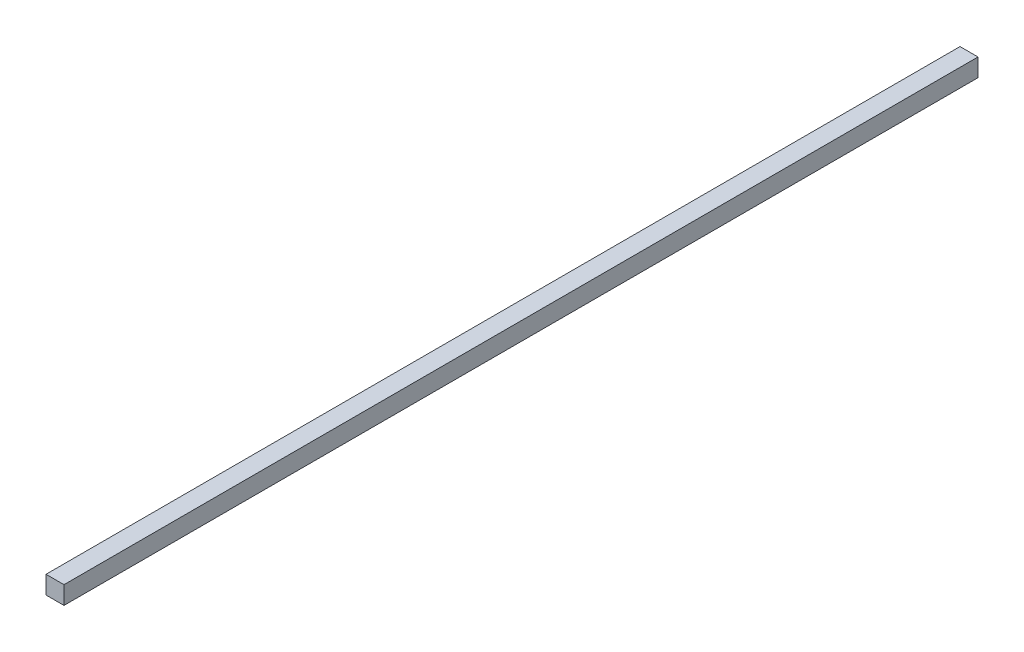
SolidWorks part; units mm, degrees
ref_plane "Front Plane" through (0, 0, 0) normal (0, 0, 1) x (1, 0, 0)
ref_plane "Top Plane" through (0, 0, 0) normal (0, 1, 0) x (1, 0, 0)
ref_plane "Right Plane" through (0, 0, 0) normal (1, 0, 0) x (0, 0, -1)
sketch "Sketch1" plane through (0, 0, 0) normal (0, 0, 1) x (1, 0, 0)
  line L0 (-3, 0) -> (3, 0) construction
  line L1 (0, -3) -> (0, 3) construction
  line L5 (-3, 3) -> (3, 3) construction
  line L7 (-3, 3) -> (-3, -3) construction
  line L8 (3, -3) -> (3, 3) construction
  line L13 (-3, -3) -> (3, -3) construction
  point P0 (0, 0)
  point P4 (0, 0)
  point P9 (0, 0)
  point P22 (0, 3)
  dimension "Thickness" = 6
  dimension "D1" = 6
sketch "Sketch2" plane through (0, 0, 0) normal (0, 1, 0) x (0, 0, -1)
  line L0 (152.4, 0) -> (-152.4, 0) construction
  line L2 (-152.4, 3) -> (152.4, 3) construction
  line L3 (-152.4, 3) -> (-152.4, -3) construction
  line L4 (-152.4, -3) -> (152.4, -3) construction
  line L5 (152.4, 3) -> (152.4, -3) construction
  line L6 (-152.4, 3) -> (152.4, -3) construction
  line L7 (-152.4, -3) -> (152.4, 3) construction
  point P4 (0, 0)
  point P7 (0, 0)
  point P12 (-145.5, 3)
  point P13 (145.5, 3)
  dimension "Length" = 304.8
  dimension "Width" = 6
  dimension "D1" = 6.9
  dimension "D2" = 6.9
sketch "Sketch3" plane through (0, 0, 0) normal (0, 0, 1) x (1, 0, 0)
  line L3 (-3, 3) -> (3, 3)
  line L17 (3, 3) -> (3, -3)
  line L18 (3, -3) -> (-3, -3)
  line L19 (-3, -3) -> (-3, 3)
extrude "Boss-Extrude1" add sketch "Sketch3" along normal mid plane 304.8
equation "\"D1@Boss-Extrude1\" = \"Length@Sketch2\""
equation "\"D1@Sketch1\"=\"Width@Sketch2\""
equation "\"D1@Sketch2\"=\"Width@Sketch2\"*1.15"
equation "\"D2@Sketch2\"=\"D1@Sketch2\""
